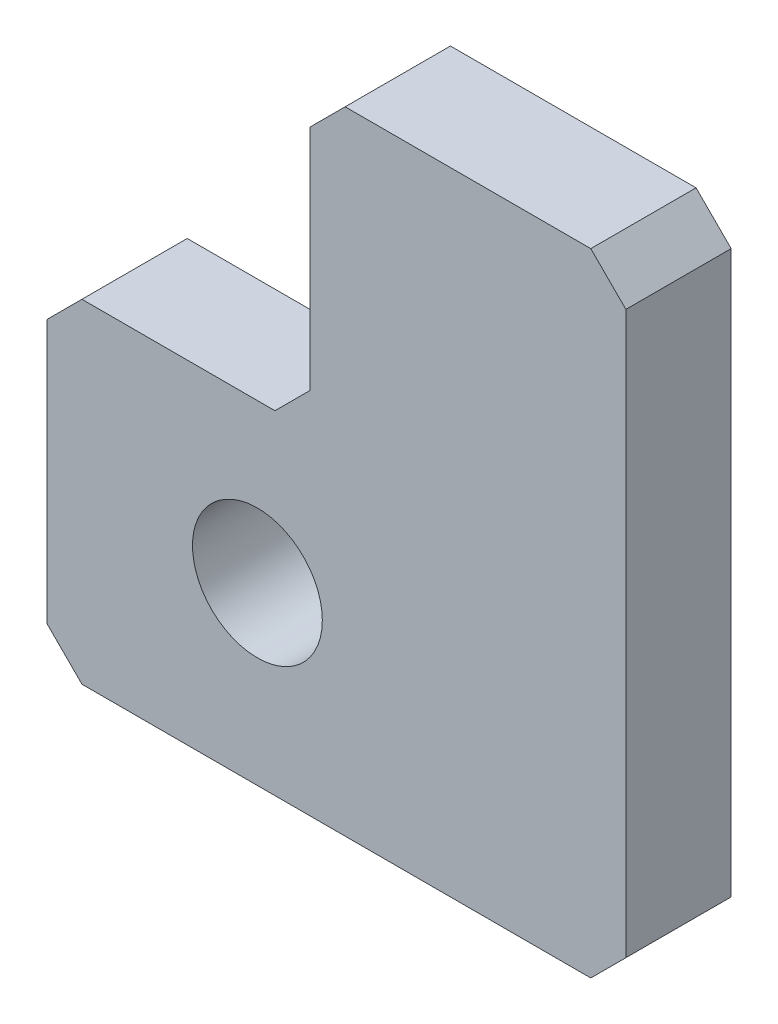
SolidWorks part; units mm, degrees
ref_plane "Front Plane" through (0, 0, 0) normal (0, 0, 1) x (1, 0, 0)
ref_plane "Top Plane" through (0, 0, 0) normal (0, 1, 0) x (1, 0, 0)
ref_plane "Right Plane" through (0, 0, 0) normal (1, 0, 0) x (0, 0, -1)
sketch "Sketch3" plane through (-178.5203, 0, 0) normal (-1, 0, 0) x (0, 0, 1)
  line L0 (-3, 14.6846) -> (-5.2502, 12.8844)
  line L1 (-3, 17.6344) -> (0, 17.6344)
  line L2 (-3, 17.6344) -> (-3, 14.6846)
  line L3 (-3, 8.1344) -> (0, 8.1344)
  line L4 (0, 17.6344) -> (0, 8.1344)
  line L5 (-5.2502, 12.8844) -> (-3, 11.0842)
  line L6 (-3, 11.0842) -> (-3, 8.1344)
  point P14 (0, 12.8844)
  dimension "D1" = 3
  dimension "D2" = 9.5
  dimension "D3" = 77.32
  dimension "D4" = 2.2502
extrude "Boss-Extrude3" add sketch "Sketch3" against normal blind 12 contours L3 L4 L1 L2 L0 L5 L6
sketch "Sketch5" plane through (-166.5203, 0, 0) normal (1, 0, 0) x (0, 0, -1)
  line L1 (0, 26.1344) -> (3, 26.1344)
  line L2 (0, 26.1344) -> (0, 8.1344)
  line L3 (0, 8.1344) -> (3, 8.1344)
  line L4 (3, 26.1344) -> (3, 8.1344)
  dimension "D1" = 18
  dimension "D2" = 3
extrude "Boss-Extrude4" add sketch "Sketch5" along normal mid plane 9
chamfer "Chamfer1" distance 1 angle 45 6 edges at (-171.0203, 17.6344, -1.5) (-171.0203, 26.1344, -1.5) (-162.0203, 26.1344, -1.5) (-162.0203, 8.1344, -1.5) (-178.5203, 8.1344, -1.5) (-178.5203, 17.6344, -1.5)
sketch "Sketch4" plane through (0, 0, 0) normal (0, 0, 1) x (1, 0, 0)
  line L0 (-178.5203, 16.6344) -> (-178.5203, 9.1344) construction
  line L1 (-172.0203, 17.6344) -> (-177.5203, 17.6344) construction
  circle A0 centre (-172.5203, 13.1344) radius 1.85
  dimension "D1" = 3.7
  dimension "D2" = 6
  dimension "D3" = 4.5
extrude "Cut-Extrude1" cut sketch "Sketch4" against normal blind 12
